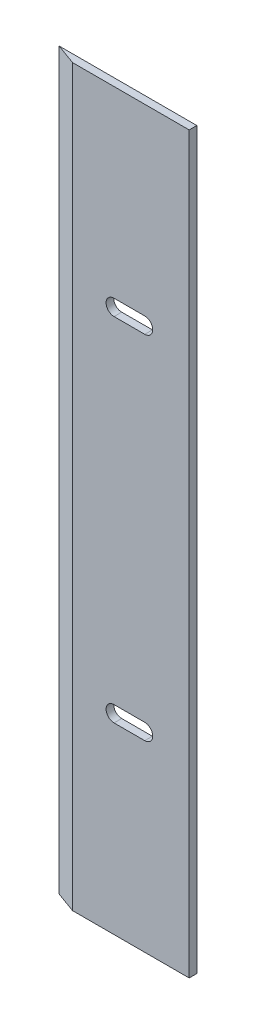
SolidWorks part; units mm, degrees
ref_plane "Спереди" through (0, 0, 0) normal (0, 0, 1) x (1, 0, 0)
ref_plane "Сверху" through (0, 0, 0) normal (0, 1, 0) x (1, 0, 0)
ref_plane "Справа" through (0, 0, 0) normal (1, 0, 0) x (0, 0, -1)
sketch "Эскиз1" plane through (0, 0, 0) normal (0, 0, 1) x (1, 0, 0)
  line L0 (-54.2544, 23) -> (-58.272, 23) construction
  line L1 (-48.4463, 48) -> (-66.4463, 48)
  line L2 (-48.4463, 48) -> (-48.4463, -48)
  line L3 (-48.4463, -48) -> (-66.4463, -48)
  line L4 (-66.4463, 48) -> (-66.4463, -48)
  line L5 (-54.2544, 21.9629) -> (-58.272, 21.9629)
  line L6 (-54.2544, 24.0371) -> (-58.272, 24.0371)
  line L7 (-48.4463, 0) -> (-59.9363, 0) construction
  line L8 (-54.2544, -23) -> (-58.272, -23) construction
  line L9 (-54.2544, -21.9629) -> (-58.272, -21.9629)
  line L10 (-54.2544, -24.0371) -> (-58.272, -24.0371)
  arc A2 (-54.2544, 21.9629) -> (-54.2544, 24.0371) centre (-54.2544, 23) ccw
  arc A3 (-58.272, 24.0371) -> (-58.272, 21.9629) centre (-58.272, 23) ccw
  arc A4 (-54.2544, -21.9629) -> (-54.2544, -24.0371) centre (-54.2544, -23) cw
  arc A5 (-58.272, -24.0371) -> (-58.272, -21.9629) centre (-58.272, -23) cw
  point P12 (-56.2632, 23)
  point P20 (-56.2632, -23)
extrude "Бобышка-Вытянуть1" add sketch "Эскиз1" along normal blind 1
sketch "Эскиз2" plane through (0, 48, 0) normal (0, 1, 0) x (1, 0, 0)
  line L0 (-66.4463, 0) -> (-63.6988, -1)
  line L1 (-48.4463, -1) -> (-66.4463, -1) construction
  line L2 (-48.4463, 0) -> (-66.4463, 0) construction
  line L4 (-63.6988, -1) -> (-66.4463, -1)
  line L5 (-66.4463, -1) -> (-66.4463, 0)
  dimension "D1" = 20
extrude "Вырез-Вытянуть1" cut sketch "Эскиз2" against normal through all
